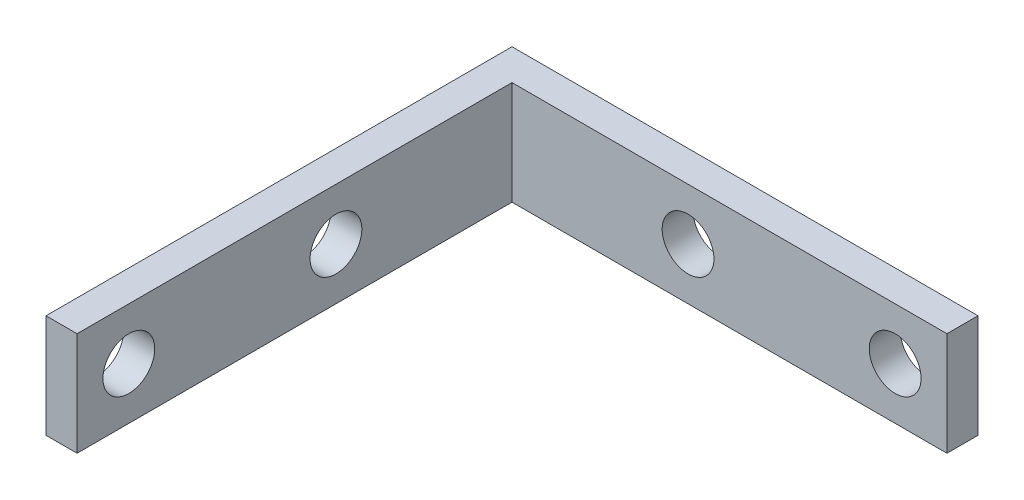
SolidWorks part; units mm, degrees
material "AISI 347 Annealed Stainless Steel (SS)"
ref_plane "Front Plane" through (0, 0, 0) normal (0, 0, 1) x (1, 0, 0)
ref_plane "Top Plane" through (0, 0, 0) normal (0, 1, 0) x (1, 0, 0)
ref_plane "Right Plane" through (0, 0, 0) normal (1, 0, 0) x (0, 0, -1)
sketch "Sketch1" plane through (0, 0, 0) normal (0, 0, 1) x (1, 0, 0)
  line L1 (0, 0) -> (45, 0)
  line L2 (0, 0) -> (0, 10)
  line L3 (0, 10) -> (45, 10)
  line L4 (45, 0) -> (45, 10)
  circle A0 centre (20, 5) radius 2.5
  circle A1 centre (40, 5) radius 2.5
  dimension "D3" = 5
  dimension "D4" = 5
  dimension "D5" = 20
  dimension "D6" = 20
  dimension "D7" = 5
  dimension "D8" = 5
  dimension "D1" = 45
  dimension "D2" = 10
extrude "Boss-Extrude1" add sketch "Sketch1" along normal blind 3
sketch "Sketch2" plane through (0, 0, 3) normal (0, 0, 1) x (1, 0, 0)
  line L0 (0, 0) -> (45, 0) construction
  line L1 (0, 10) -> (3, 10)
  line L2 (0, 10) -> (0, 0)
  line L3 (0, 0) -> (3, 0)
  line L4 (3, 10) -> (3, 0)
  dimension "D1" = 3
extrude "Boss-Extrude2" add sketch "Sketch2" along normal blind 42
sketch "Sketch3" plane through (3, 0, 0) normal (1, 0, 0) x (0, 0, -1)
  line L0 (0, 0) -> (0, 10) construction
  line L1 (-45, 10) -> (-3, 10) construction
  circle A0 centre (-20, 5) radius 2.5
  circle A1 centre (-40, 5) radius 2.5
  dimension "D1" = 5
  dimension "D2" = 5
  dimension "D3" = 20
  dimension "D4" = 20
  dimension "D5" = 5
  dimension "D6" = 5
extrude "Cut-Extrude1" cut sketch "Sketch3" against normal blind 3
